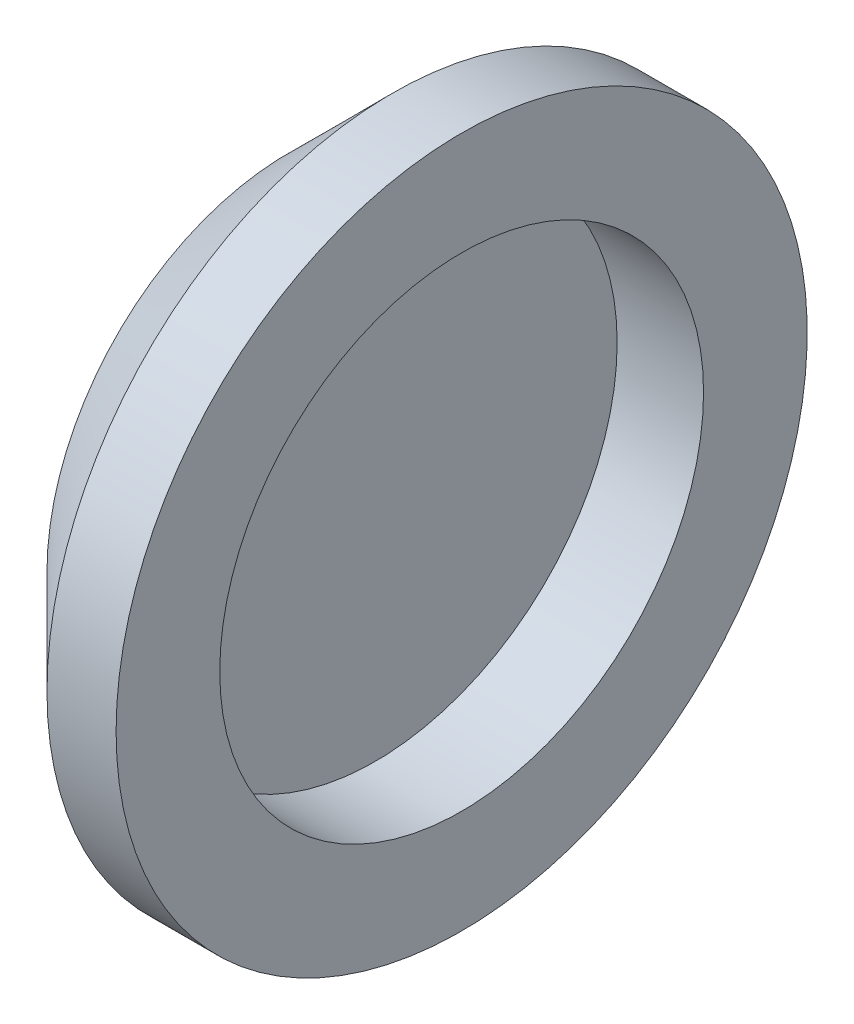
SolidWorks part; units mm, degrees
ref_plane "Front Plane" through (0, 0, 0) normal (0, 0, 1) x (1, 0, 0)
ref_plane "Top Plane" through (0, 0, 0) normal (0, 1, 0) x (1, 0, 0)
ref_plane "Right Plane" through (0, 0, 0) normal (1, 0, 0) x (0, 0, -1)
sketch "Sketch1" plane through (0, 0, 0) normal (0, 0, 1) x (1, 0, 0)
  line L0 (0, 0) -> (0, 5.08)
  line L1 (0, 5.08) -> (-1.016, 5.08)
  line L2 (-1.016, 5.08) -> (-2.54, 3.556)
  line L3 (-2.54, 3.556) -> (-2.54, 0)
  line L4 (-2.54, 0) -> (0, 0)
  dimension "D1" = 1.016
  dimension "D2" = 1.524
  dimension "D3" = 3.556
  dimension "D4" = 2.54
revolve "Revolve1" add sketch "Sketch1" angle 360 about L4
sketch "Sketch2" plane through (0, 0, 0) normal (1, 0, 0) x (0, 0, -1)
  circle A0 centre (0, 0) radius 3.556
  dimension "D1" = 7.112
extrude "Cut-Extrude1" cut sketch "Sketch2" against normal blind 1.27
